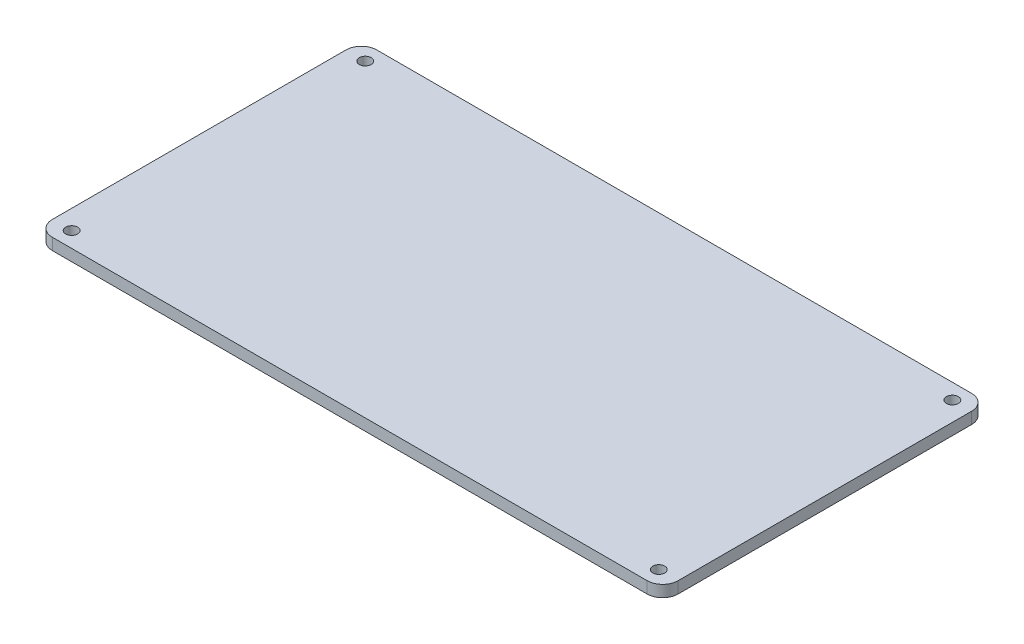
SolidWorks part; units mm, degrees
ref_plane "Front Plane" through (0, 0, 0) normal (0, 0, 1) x (1, 0, 0)
ref_plane "Top Plane" through (0, 0, 0) normal (0, 1, 0) x (1, 0, 0)
ref_plane "Right Plane" through (0, 0, 0) normal (1, 0, 0) x (0, 0, -1)
sketch "Sketch1" plane through (0, 0, 0) normal (0, 1, 0) x (1, 0, 0)
  line L0 (-20.1659, 0) -> (17.8628, 0) construction
  line L1 (-77, -42) -> (77, -42)
  line L2 (-81, -38) -> (-81, 38)
  line L3 (-77, 42) -> (77, 42)
  line L4 (81, -38) -> (81, 38)
  line L5 (-81, -42) -> (81, 42) construction
  line L6 (-81, 42) -> (81, -42) construction
  line L7 (0, 22.6208) -> (0, -11.8303) construction
  arc A0 (-77, -42) -> (-81, -38) centre (-77, -38) cw
  arc A1 (-81, 38) -> (-77, 42) centre (-77, 38) cw
  arc A2 (77, -42) -> (81, -38) centre (77, -38) ccw
  arc A3 (77, 42) -> (81, 38) centre (77, 38) cw
  circle A4 centre (-76, 38) radius 1.55
  circle A5 centre (-76, -38) radius 1.55
  circle A6 centre (76, 38) radius 1.55
  circle A7 centre (76, -38) radius 1.55
  point P0 (0, 0)
  dimension "D3" = 4
  dimension "D4" = 76
  dimension "D5" = 38
  dimension "D6" = 3.1
  dimension "D1" = 162
  dimension "D2" = 84
extrude "Boss-Extrude1" add sketch "Sketch1" along normal blind 3
